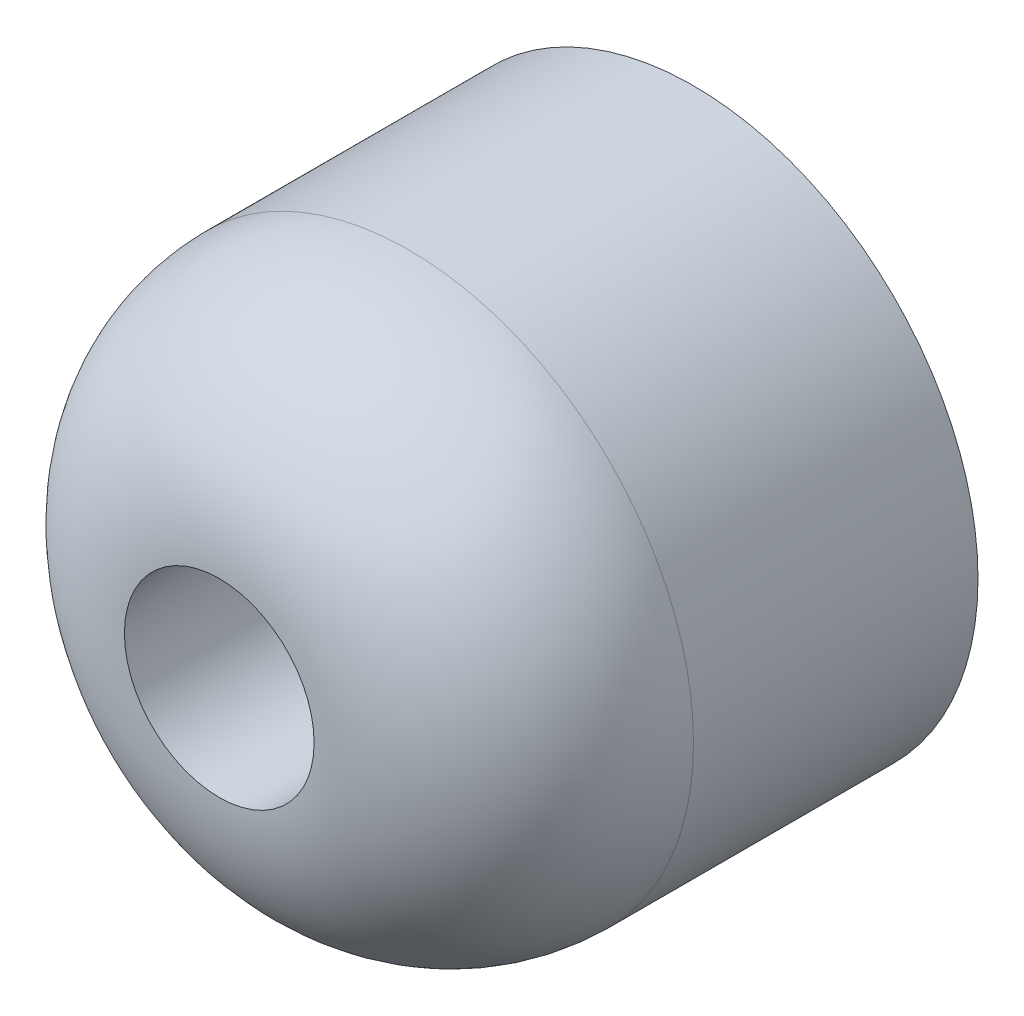
SolidWorks part; units mm, degrees
ref_plane "Front Plane" through (0, 0, 0) normal (0, 0, 1) x (1, 0, 0)
ref_plane "Top Plane" through (0, 0, 0) normal (0, 1, 0) x (1, 0, 0)
ref_plane "Right Plane" through (0, 0, 0) normal (1, 0, 0) x (0, 0, -1)
sketch "Sketch1" plane through (0, 0, 0) normal (0, 0, 1) x (1, 0, 0)
  circle A0 centre (0, 0) radius 3
  dimension "D1" = 6
extrude "Boss-Extrude1" add sketch "Sketch1" along normal blind 5
fillet "Fillet3" radius 2 1 edges at (3, 0, 5)
sketch "Sketch2" plane through (0, 0, 0) normal (0, 0, -1) x (-1, 0, 0)
  circle A0 centre (0, 0) radius 1
  dimension "D1" = 2
extrude "Cut-Extrude1" cut sketch "Sketch2" against normal blind 10
